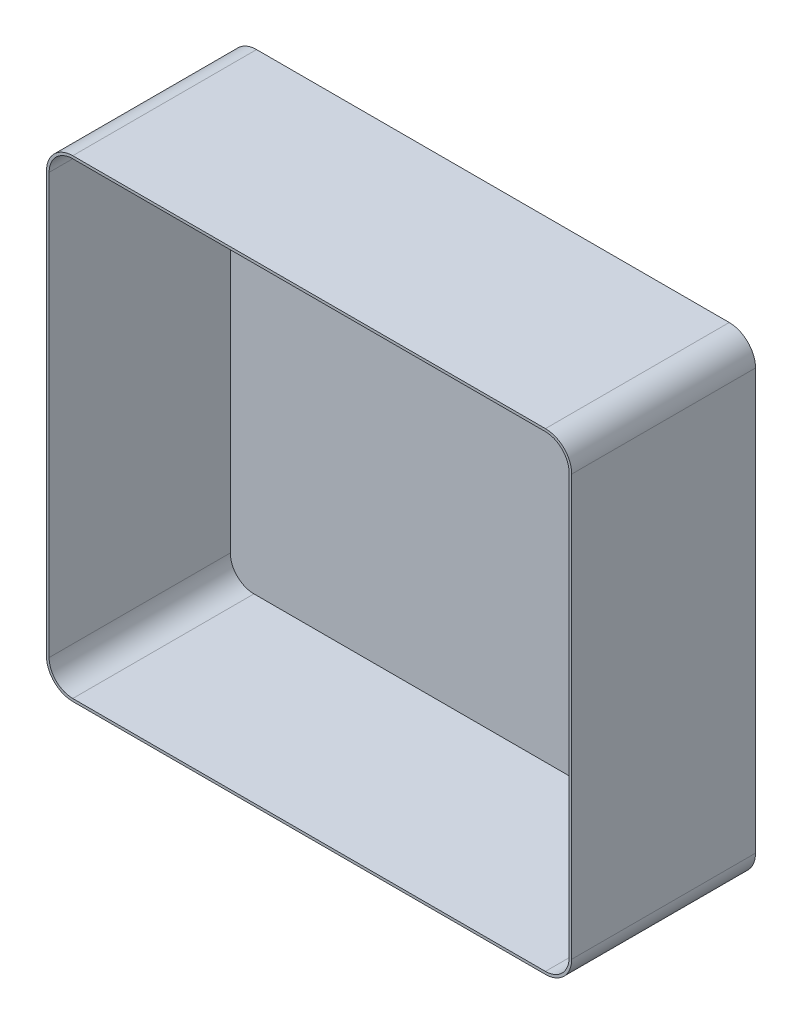
SolidWorks part; units mm, degrees
ref_plane "前视基准面" through (0, 0, 0) normal (0, 0, 1) x (1, 0, 0)
ref_plane "上视基准面" through (0, 0, 0) normal (0, 1, 0) x (1, 0, 0)
ref_plane "右视基准面" through (0, 0, 0) normal (1, 0, 0) x (0, 0, -1)
sketch "草图1" plane through (0, 0, 0) normal (0, 0, 1) x (1, 0, 0)
  line L1 (-90, -90) -> (90, -90)
  line L2 (-100, -80) -> (-100, 80)
  line L3 (-90, 90) -> (90, 90)
  line L4 (100, -80) -> (100, 80)
  line L5 (-100, -90) -> (100, 90) construction
  line L6 (-100, 90) -> (100, -90) construction
  line L10 (-101.3379, -88.5134) -> (98.6621, 91.4866)
  line L11 (-98.6621, 91.4866) -> (101.3379, -88.5134)
  arc A0 (90, -90) -> (100, -80) centre (90, -80) ccw
  arc A1 (90, 90) -> (100, 80) centre (90, 80) cw
  arc A2 (-90, -90) -> (-100, -80) centre (-90, -80) cw
  arc A3 (-100, 80) -> (-90, 90) centre (-90, 80) cw
  point P0 (0, 0)
  dimension "D3" = 10
  dimension "D1" = 180
  dimension "D2" = 200
  dimension "D4" = 2
extrude "凸台-拉伸1" add sketch "草图1" along normal blind 70
shell "抽壳1" thickness 1
